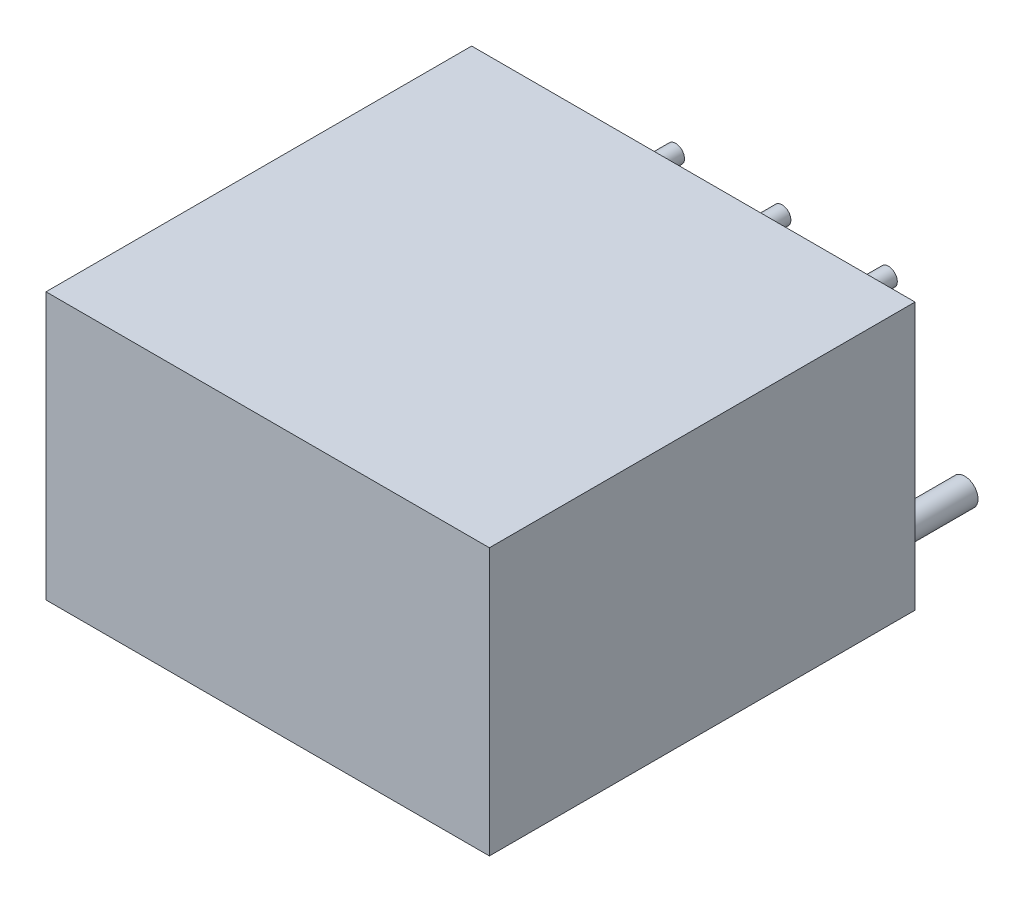
SolidWorks part; units mm, degrees
ref_plane "Спереди" through (0, 0, 0) normal (0, 0, 1) x (1, 0, 0)
ref_plane "Сверху" through (0, 0, 0) normal (0, 1, 0) x (1, 0, 0)
ref_plane "Справа" through (0, 0, 0) normal (1, 0, 0) x (0, 0, -1)
sketch "Эскиз2" plane through (0, 0, 0) normal (0, 0, 1) x (1, 0, 0)
  line L1 (-29.5791, 25.0682) -> (-4.5791, 25.0682)
  line L2 (-29.5791, 25.0682) -> (-29.5791, 10.0182)
  line L3 (-29.5791, 10.0182) -> (-4.5791, 10.0182)
  line L4 (-4.5791, 25.0682) -> (-4.5791, 10.0182)
extrude "Бобышка-Вытянуть2" add sketch "Эскиз2" along normal blind 24
sketch "Эскиз3" plane through (0, 0, 0) normal (0, 0, -1) x (-1, 0, 0)
  line L0 (4.5791, 25.0682) -> (29.5791, 25.0682) construction
  line L1 (29.5791, 10.0182) -> (4.5791, 10.0182) construction
  line L2 (29.5791, 25.0682) -> (29.5791, 10.0182) construction
  line L3 (4.5791, 10.0182) -> (4.5791, 25.0682) construction
  circle A0 centre (6.7791, 12.2182) radius 0.75
  circle A1 centre (11.0791, 14.5682) radius 0.5
  circle A2 centre (17.0791, 14.5682) radius 0.5
  circle A3 centre (11.0791, 20.5682) radius 0.5
  circle A4 centre (17.0791, 20.5682) radius 0.5
  circle A5 centre (23.0791, 20.5682) radius 0.5
  circle A6 centre (23.0791, 14.5682) radius 0.5
  circle A7 centre (27.3791, 12.2182) radius 0.75
  dimension "D9" = 1.5
  dimension "D10" = 1.5
  dimension "D1" = 4.5
  dimension "D2" = 6
  dimension "D3" = 2.2
  dimension "D4" = 2.2
  dimension "D5" = 2.2
  dimension "D6" = 6.5
  dimension "D7" = 6
  dimension "D8" = 6
extrude "Бобышка-Вытянуть3" add sketch "Эскиз3" along normal blind 5
